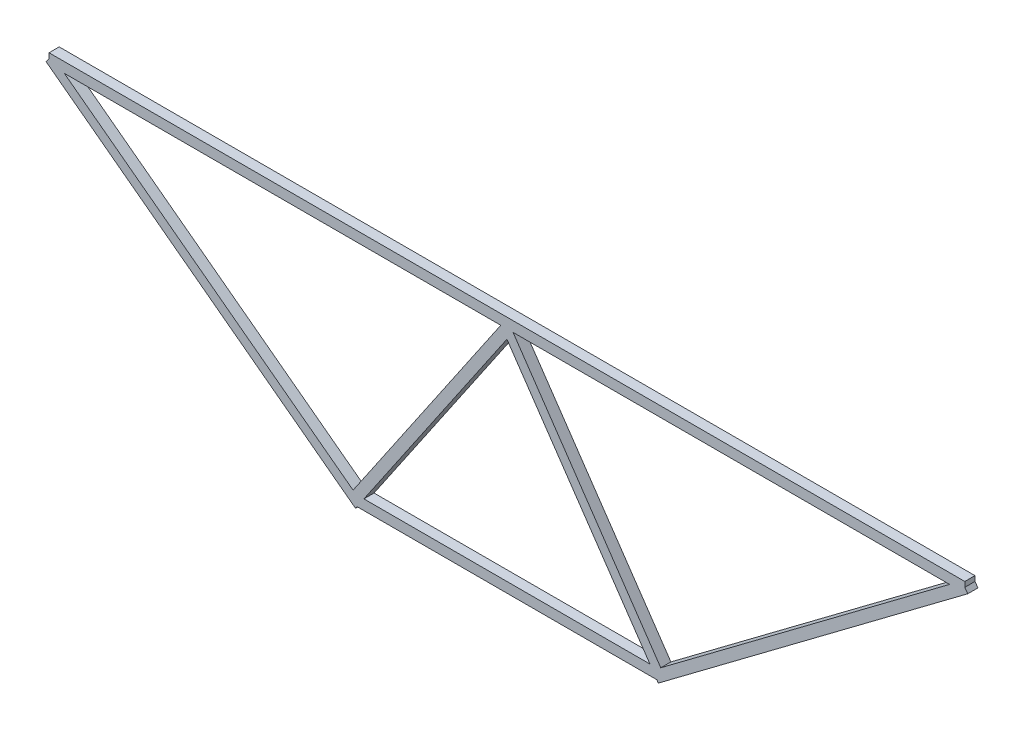
SolidWorks part; units mm, degrees
material "Plain Carbon Steel"
ref_plane "Front Plane" through (0, 0, 0) normal (0, 0, 1) x (1, 0, 0)
ref_plane "Top Plane" through (0, 0, 0) normal (0, 1, 0) x (1, 0, 0)
ref_plane "Right Plane" through (0, 0, 0) normal (1, 0, 0) x (0, 0, -1)
sketch "Sketch1" plane through (0, 0, 0) normal (0, 0, 1) x (1, 0, 0)
  line L0 (0, 0) -> (1200, 0)
  dimension "D1" = 1200
extrude "Extrude-Thin1" add sketch "Sketch1" along normal mid plane 13.3 thin
sketch "Sketch2" plane through (0, 0, 0) normal (0, 0, 1) x (1, 0, 0)
  line L0 (400, -300) -> (800, -300)
  line L1 (0, 0) -> (1200, 0) construction
  point P4 (600, 0)
  point P5 (600, -300)
  dimension "D1" = 400
  dimension "D2" = 300
extrude "Extrude-Thin2" add sketch "Sketch2" along normal mid plane 13.3 separate body thin
sketch "Sketch3" plane through (0, 0, 0) normal (0, 0, 1) x (1, 0, 0)
  line L0 (400, -306.65) -> (0, -6.65)
  line L1 (400, -313.3) -> (400, -300) construction
  line L2 (0, -13.3) -> (0, 0) construction
  line L6 (800, -300) -> (800, -313.3) construction
  line L7 (800, -306.65) -> (1200, -6.65)
  line L8 (1200, 0) -> (1200, -13.3) construction
  line L9 (400, -306.65) -> (600, -13.3)
  line L10 (0, -13.3) -> (1200, -13.3) construction
  line L11 (600, -13.3) -> (800, -306.65)
extrude "Extrude-Thin3" add sketch "Sketch3" along normal mid plane 13.3 thin contours L0 L9 L11 L7 thin type mid plane wall 13.3
